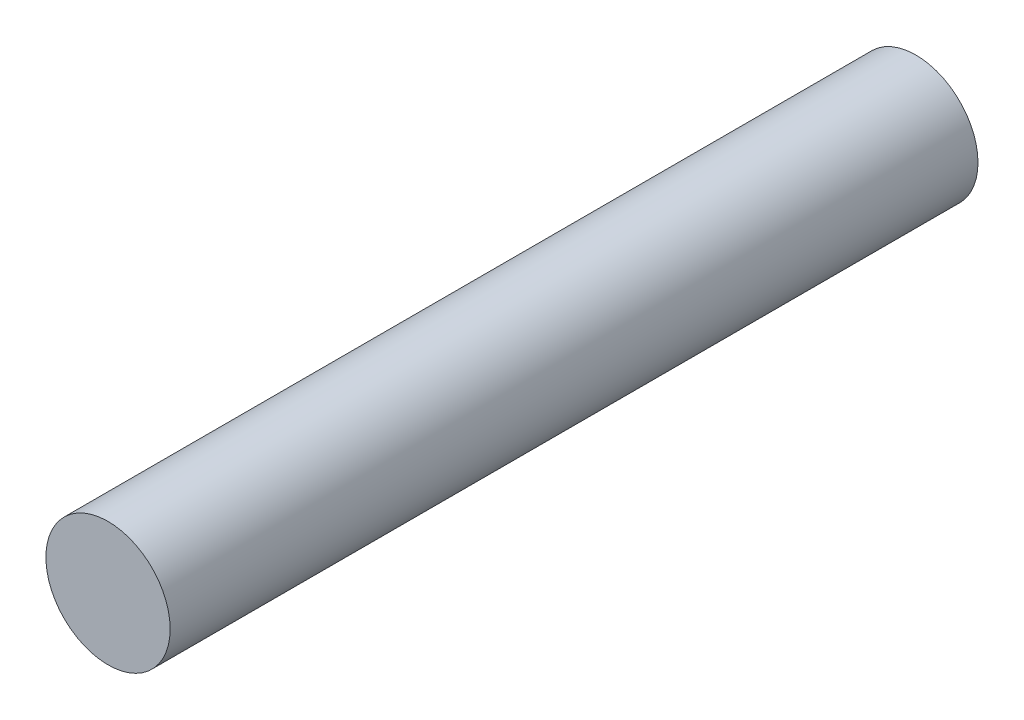
SolidWorks part; units mm, degrees
ref_plane "Front Plane" through (0, 0, 0) normal (0, 0, 1) x (1, 0, 0)
ref_plane "Top Plane" through (0, 0, 0) normal (0, 1, 0) x (1, 0, 0)
ref_plane "Right Plane" through (0, 0, 0) normal (1, 0, 0) x (0, 0, -1)
sketch "Sketch1" plane through (0, 0, 0) normal (0, 0, 1) x (1, 0, 0)
  circle A0 centre (0, 0) radius 5
  dimension "D1" = 10
extrude "Boss-Extrude1" add sketch "Sketch1" along normal blind 65
